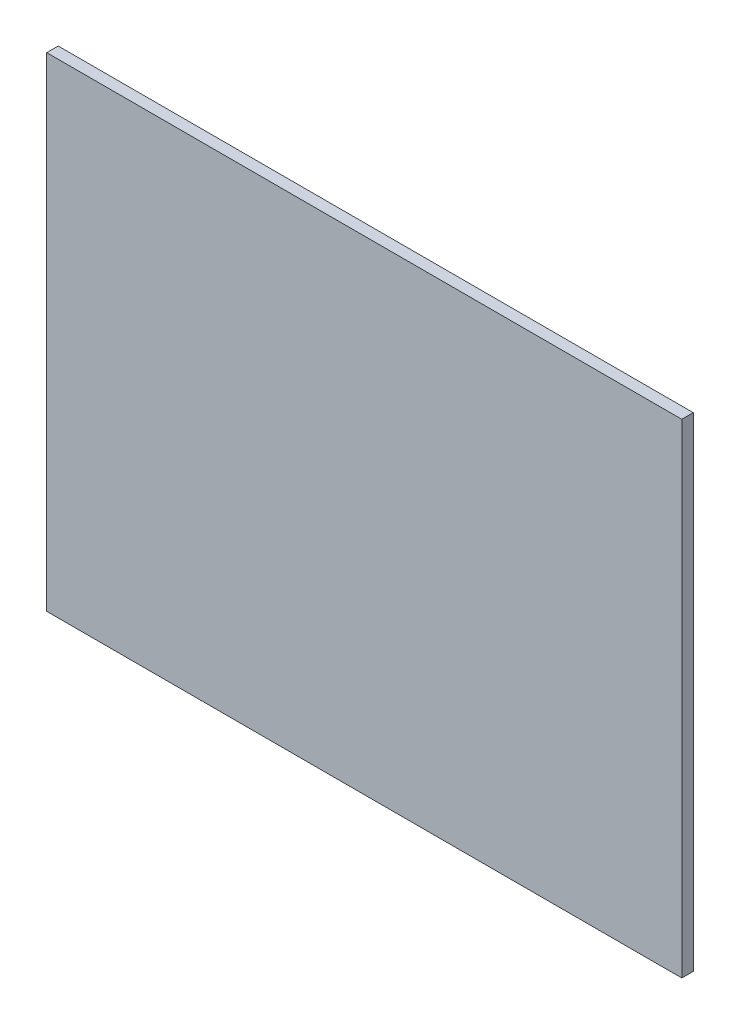
SolidWorks part; units mm, degrees
material "Kiefer"
ref_plane "Ebene vorne" through (0, 0, 0) normal (0, 0, 1) x (1, 0, 0)
ref_plane "Ebene oben" through (0, 0, 0) normal (0, 1, 0) x (1, 0, 0)
ref_plane "Ebene rechts" through (0, 0, 0) normal (1, 0, 0) x (0, 0, -1)
sketch "Skizze1" plane through (0, 0, 0) normal (0, 0, 1) x (1, 0, 0)
  line L0 (0, 0) -> (0, 40.512) construction
  line L2 (525, 400) -> (-525, 400)
  line L3 (525, 400) -> (525, -400)
  line L4 (525, -400) -> (-525, -400)
  line L5 (-525, 400) -> (-525, -400)
  line L6 (525, 400) -> (-525, -400) construction
  line L7 (525, -400) -> (-525, 400) construction
  dimension "D1" = 1050
  dimension "D2" = 800
extrude "Aufsatz-Linear austragen1" add sketch "Skizze1" along normal mid plane 19
